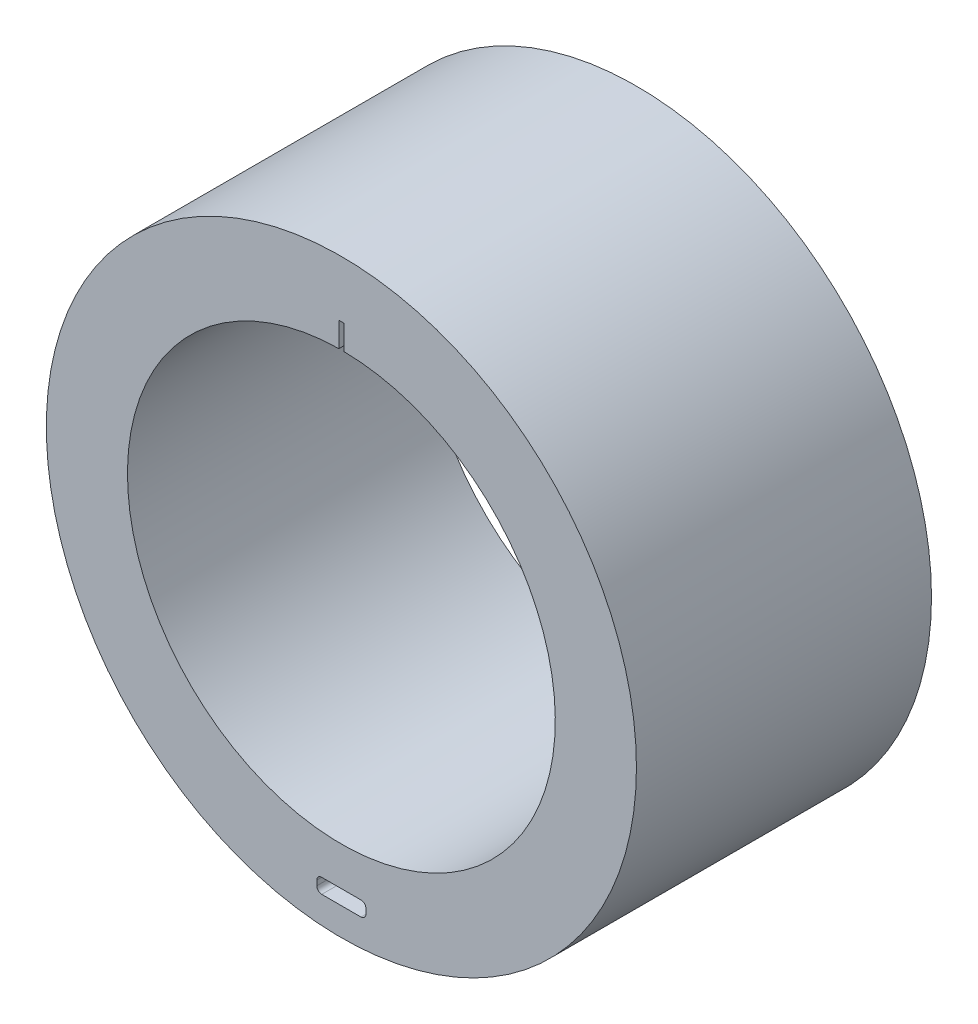
SolidWorks part; units mm, degrees
ref_plane "Front Plane" through (0, 0, 0) normal (0, 0, 1) x (1, 0, 0)
ref_plane "Top Plane" through (0, 0, 0) normal (0, 1, 0) x (1, 0, 0)
ref_plane "Right Plane" through (0, 0, 0) normal (1, 0, 0) x (0, 0, -1)
ref_plane "Plane1"
sketch "Sketch1" plane through (0, 0, 0) normal (0, 0, 1) x (1, 0, 0)
  circle A0 centre (0, 0) radius 60
  circle A1 centre (0, 0) radius 43.5
  dimension "D1" = 87
  dimension "D2" = 120
extrude "Extrusion1" add sketch "Sketch1" along normal blind 60 contours A0 A1
ref_plane "Plane2"
ref_plane "Plane3"
sketch "Sketch3" plane through (0, 0, 60) normal (0, 0, 1) x (1, 0, 0)
  line L0 (-0.5, 48.5) -> (-0.5, 43.4971)
  line L1 (0.5, 43.4971) -> (0.5, 48.5)
  line L2 (0.5, 48.5) -> (-0.5, 48.5)
  arc A0 (0.5, 43.4971) -> (-0.5, 43.4971) centre (0, 0) ccw
extrude "Extrusion3" cut sketch "Sketch3" against normal blind 60
sketch "Sketch4" plane through (0, 0, 0) normal (0, 0, -1) x (-1, 0, 0)
  line L0 (50.3187, 0) -> (60, 0)
  line L1 (0, 0) -> (0, -60)
  line L2 (-50.3161, -0.5063) -> (-59.9979, -0.5063)
  line L3 (55.3161, -14.0063) -> (45.3161, 12.9937) construction
  line L4 (-54.3161, 12.9937) -> (-46.3161, 12.9937)
  line L5 (-55.3161, 11.9937) -> (-55.3161, -13.0063)
  line L6 (-54.3161, -14.0063) -> (-46.3161, -14.0063)
  line L7 (-45.3161, 11.9937) -> (-45.3161, -13.0063)
  line L8 (-55.3161, 12.9937) -> (-45.3161, -14.0063) construction
  line L9 (-55.3161, -14.0063) -> (-45.3161, 12.9937) construction
  line L10 (55.3161, 12.9937) -> (45.3161, -14.0063) construction
  line L11 (45.3161, 11.9937) -> (45.3161, -13.0063)
  line L12 (54.3161, -14.0063) -> (46.3161, -14.0063)
  line L13 (55.3161, 11.9937) -> (55.3161, -13.0063)
  line L14 (54.3161, 12.9937) -> (46.3161, 12.9937)
  circle A0 centre (0, 0) radius 60 construction
  arc A1 (-50.3161, -0.5063) -> (50.3187, 0) centre (0, 0) ccw
  arc A2 (-54.3161, 12.9937) -> (-55.3161, 11.9937) centre (-54.3161, 11.9937) ccw
  arc A3 (-55.3161, -13.0063) -> (-54.3161, -14.0063) centre (-54.3161, -13.0063) ccw
  arc A4 (-46.3161, -14.0063) -> (-45.3161, -13.0063) centre (-46.3161, -13.0063) ccw
  arc A5 (-45.3161, 11.9937) -> (-46.3161, 12.9937) centre (-46.3161, 11.9937) ccw
  arc A6 (45.3161, 11.9937) -> (46.3161, 12.9937) centre (46.3161, 11.9937) cw
  arc A7 (46.3161, -14.0063) -> (45.3161, -13.0063) centre (46.3161, -13.0063) cw
  arc A8 (55.3161, -13.0063) -> (54.3161, -14.0063) centre (54.3161, -13.0063) cw
  arc A9 (54.3161, 12.9937) -> (55.3161, 11.9937) centre (54.3161, 11.9937) cw
  point P7 (-50.3161, -0.5063)
  point P43 (50.3161, -0.5063)
  dimension "D3" = 1
  dimension "D1" = 27
  dimension "D2" = 10
extrude "Cut-Extrude2" cut sketch "Sketch4" against normal blind 55 contours L7 A5 L4 A2 L5 L2 A1 L6 A4 | L5 A3 L6 A1 L2 | A8 L13 L0 A1 L12 | A9 L14 A6 L11 A7 L12 A1 L0 L13
sketch "Sketch5" plane through (0, 0, 0) normal (0, 0, -1) x (-1, 0, 0)
  line L3 (-52.5188, -14.0063) -> (-48.5188, -14.0063)
  line L4 (48.5188, -14.0063) -> (51.634, -14.0063)
  arc A3 (-52.5188, -14.0063) -> (51.634, -14.0063) centre (-0.4424, -1.7467) ccw
  arc A4 (-48.5188, -14.0063) -> (48.5188, -14.0063) centre (0, 0) ccw
  point P1 (0, 0)
  point P3 (-53.479, 1.5)
  point P4 (53.479, 1.5)
  point P5 (-52, 0)
  point P6 (52, 0)
  point P7 (52, 0)
  point P9 (-50.4777, -1.5)
  point P10 (50.4777, -1.5)
  dimension "D1" = 4
extrude "Cut-Extrude3" cut sketch "Sketch5" against normal blind 10 contours A4 L4 A3 L3
sketch "Sketch7" plane through (0, 0, 0) normal (0, 0, -1) x (-1, 0, 0)
  line L0 (21.086, -51.0805) -> (42.5995, -36.4803)
  line L1 (39.4962, -30.1266) -> (42.8654, -35.0913)
  line L3 (16.5936, -44.4609) -> (38.1072, -29.8607)
  line L7 (16.3277, -45.8499) -> (19.697, -50.8146)
  arc A10 (16.5936, -44.4609) -> (16.3277, -45.8499) centre (17.1551, -45.2883) ccw
  arc A11 (19.697, -50.8146) -> (21.086, -51.0805) centre (20.5244, -50.253) ccw
  arc A12 (42.5995, -36.4803) -> (42.8654, -35.0913) centre (42.038, -35.6528) ccw
  arc A13 (39.4962, -30.1266) -> (38.1072, -29.8607) centre (38.6687, -30.6881) ccw
  dimension "D1" = 1
extrude "Cut-Extrude4" cut sketch "Sketch7" against normal blind 35 contours L7 A11 L0 A12 L1 A13 L3 A10
sketch "Sketch8" plane through (0, 0, 0) normal (0, 0, -1) x (-1, 0, 0)
  line L0 (0, 0) -> (0, -60)
  line L2 (-4, -54.3484) -> (4, -54.3484)
  line L3 (-5, -53.3484) -> (-5, -52.3484)
  line L4 (-4, -51.3484) -> (4, -51.3484)
  line L5 (5, -53.3484) -> (5, -52.3484)
  line L6 (-5, -54.3484) -> (5, -51.3484) construction
  line L7 (-5, -51.3484) -> (5, -54.3484) construction
  circle A0 centre (0, 0) radius 60 construction
  arc A1 (4, -54.3484) -> (5, -53.3484) centre (4, -53.3484) ccw
  arc A2 (-5, -53.3484) -> (-4, -54.3484) centre (-4, -53.3484) ccw
  arc A3 (-4, -51.3484) -> (-5, -52.3484) centre (-4, -52.3484) ccw
  arc A4 (5, -52.3484) -> (4, -51.3484) centre (4, -52.3484) ccw
  point P5 (0, -52.8484)
  dimension "D3" = 1
  dimension "D4" = 1
  dimension "D5" = 1
  dimension "D6" = 1
  dimension "D1" = 3
  dimension "D2" = 10
extrude "Cut-Extrude5" cut sketch "Sketch8" against normal through all contours L4 A3 L3 A2 L2 L0 | L5 A4 L4 L0 L2 A1
sketch "Sketch9" plane through (0, 0, 0) normal (0, 0, -1) x (-1, 0, 0)
  line L2 (-46.5417, -20.6566) -> (-48.1748, -21.8112)
  line L3 (-34.9963, -36.9877) -> (-36.6294, -38.1422)
  line L4 (-33.7999, -30.0186) -> (-39.5726, -21.853)
  line L5 (-43.5985, -36.9458) -> (-49.3712, -28.7803)
  arc A1 (-48.1748, -21.8112) -> (-49.3712, -28.7803) centre (-45.2884, -25.8939) ccw
  arc A2 (-46.5417, -20.6566) -> (-39.5726, -21.853) centre (-43.6553, -24.7394) cw
  arc A3 (-36.6294, -38.1422) -> (-43.5985, -36.9458) centre (-39.5157, -34.0595) cw
  arc A4 (-33.7999, -30.0186) -> (-34.9963, -36.9877) centre (-37.8826, -32.9049) cw
  point P7 (-5.7727, 8.1655)
  point P8 (-54.7658, -26.4708)
  point P9 (5.7727, -8.1655)
  point P10 (-43.2204, -42.8018)
  dimension "D5" = 5
  dimension "D6" = 5
  dimension "D7" = 5
  dimension "D8" = 5
extrude "Cut-Extrude6" cut sketch "Sketch9" against normal blind 30 contours A2 L4 A4 L3 A3 L5 A1 L2
sketch "Sketch10" plane through (0, 0, 0) normal (0, 0, -1) x (-1, 0, 0)
  line L1 (-15.6196, -50.0653) -> (-29.1529, -43.5961)
  line L2 (-27.859, -40.8895) -> (-30.4467, -46.3028)
  line L3 (-14.3258, -47.3587) -> (-16.9135, -52.772)
  line L4 (-14.7967, -46.0252) -> (-26.5255, -40.4185)
  line L5 (-18.247, -53.2429) -> (-29.9758, -47.6363)
  line L7 (-17.3448, -53.6742) -> (-30.878, -47.205) construction
  line L9 (-13.8945, -46.4565) -> (-27.4278, -39.9872) construction
  arc A1 (-16.9135, -52.772) -> (-18.247, -53.2429) centre (-17.8157, -52.3407) cw
  arc A2 (-30.4467, -46.3028) -> (-29.9758, -47.6363) centre (-29.5445, -46.734) ccw
  arc A3 (-26.5255, -40.4185) -> (-27.859, -40.8895) centre (-26.9568, -41.3207) ccw
  arc A4 (-14.7967, -46.0252) -> (-14.3258, -47.3587) centre (-15.228, -46.9274) cw
  arc M19 (-34.66, -36.7278) -> (17.3879, -47.4121) centre (0, 0) ccw
  arc M42 (20.0857, -51.1517) -> (-38.8291, -39.0121) centre (-0.4424, -1.7467) cw
  dimension "D5" = 1
  dimension "D6" = 1
  dimension "D7" = 1
  dimension "D8" = 1
  dimension "D3" = 4
  dimension "D4" = 4
extrude "Cut-Extrude7" cut sketch "Sketch10" against normal blind 30 contours L3 L1 L2 M42 | L2 A2 L5 A1 L3 M42 | A4 L4 A3 L2 L3 M19 | L3 L2 L1 M19
